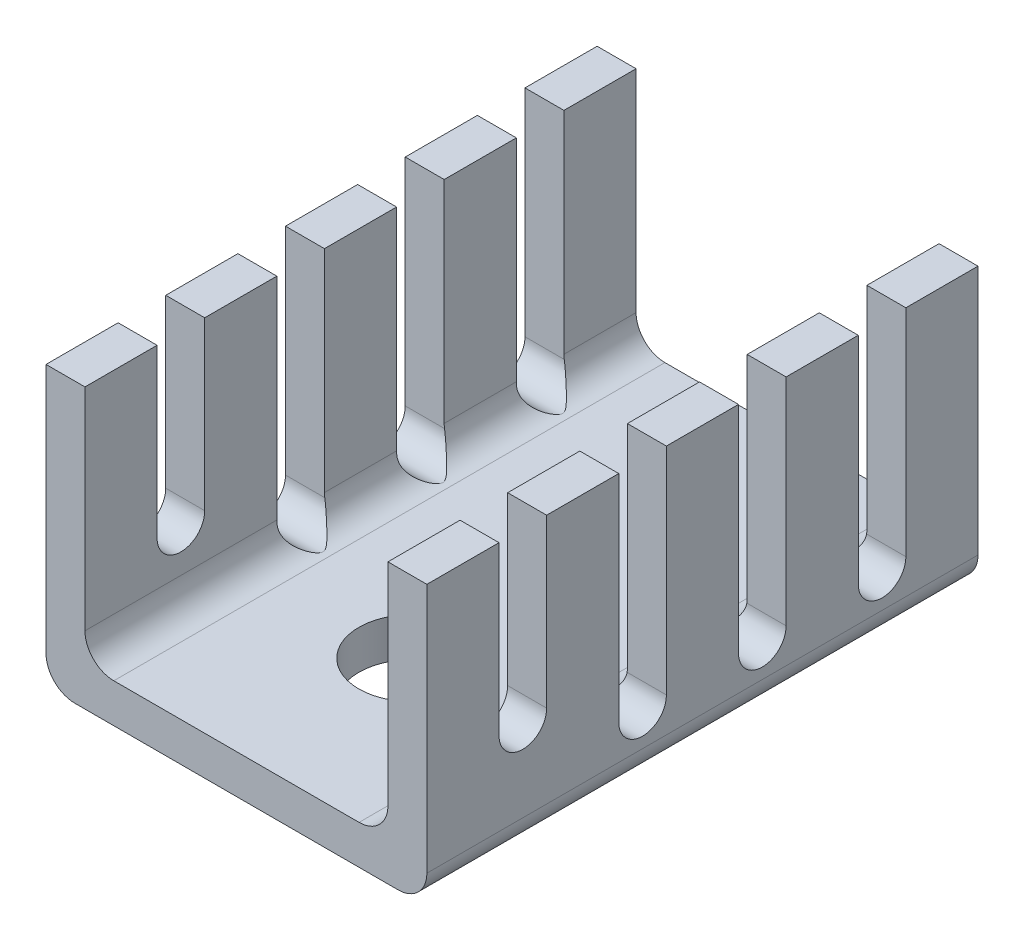
SolidWorks part; units mm, degrees
ref_plane "Front Plane" through (0, 0, 0) normal (0, 0, 1) x (1, 0, 0)
ref_plane "Top Plane" through (0, 0, 0) normal (0, 1, 0) x (1, 0, 0)
ref_plane "Right Plane" through (0, 0, 0) normal (1, 0, 0) x (0, 0, -1)
sketch "Sketch1" plane through (0, 0, 0) normal (0, 0, 1) x (1, 0, 0)
  line L0 (-5.6, 0) -> (5.6, 0)
  line L1 (6.6, 1) -> (6.6, 9.67)
  line L2 (6.6, 9.67) -> (5.25, 9.67)
  line L3 (5.25, 9.67) -> (5.25, 2.35)
  line L4 (4.25, 1.35) -> (-4.25, 1.35)
  line L5 (-5.25, 2.35) -> (-5.25, 9.67)
  line L6 (-5.25, 9.67) -> (-6.6, 9.67)
  line L7 (-6.6, 9.67) -> (-6.6, 1)
  arc A0 (-4.25, 1.35) -> (-5.25, 2.35) centre (-4.25, 2.35) cw
  arc A1 (5.25, 2.35) -> (4.25, 1.35) centre (4.25, 2.35) cw
  arc A2 (5.6, 0) -> (6.6, 1) centre (5.6, 1) ccw
  arc A3 (-5.6, 0) -> (-6.6, 1) centre (-5.6, 1) cw
  point P10 (0, 0)
  point P19 (6.6, 0)
  point P22 (-6.6, 0)
  dimension "D5" = 1
  dimension "D6" = 1
  dimension "D1" = 13.2
  dimension "D2" = 9.67
  dimension "D3" = 1.35
  dimension "D4" = 1.35
extrude "Boss-Extrude3" add sketch "Sketch1" against normal blind 19.1
sketch "Sketch3" plane through (0, 1.35, 0) normal (0, 1, 0) x (1, 0, 0)
  circle A0 centre (0.2414, 5.85) radius 1.85
  dimension "D2" = 3.7
  dimension "D1" = 5.85
extrude "Cut-Extrude2" cut sketch "Sketch3" against normal up to next
sketch "Sketch4" plane through (6.6, 0, 0) normal (1, 0, 0) x (0, 0, -1)
  line L0 (2.5, 9.67) -> (2.5, 3.88)
  line L1 (19.1, 0) -> (0, 0) construction
  line L2 (19.1, 9.67) -> (0, 9.67) construction
  line L3 (4.15, 9.67) -> (4.15, 3.88)
  line L4 (6.65, 9.67) -> (6.65, 2.2)
  line L5 (8.3, 9.67) -> (8.3, 2.2)
  line L6 (10.8, 9.67) -> (10.8, 2.2)
  line L7 (12.45, 9.67) -> (12.45, 2.2)
  line L8 (14.95, 9.67) -> (14.95, 2.2)
  line L9 (16.6, 9.67) -> (16.6, 2.2)
  line L10 (19.1, 1) -> (19.1, 9.67) construction
  line L11 (2.5, 9.67) -> (4.15, 9.67)
  line L12 (6.65, 9.67) -> (8.3, 9.67)
  line L13 (10.8, 9.67) -> (12.45, 9.67)
  line L14 (14.95, 9.67) -> (16.6, 9.67)
  arc A1 (2.5, 3.88) -> (4.15, 3.88) centre (3.325, 3.88) ccw
  arc A2 (6.65, 2.2) -> (8.3, 2.2) centre (7.475, 2.2) ccw
  arc A3 (10.8, 2.2) -> (12.45, 2.2) centre (11.625, 2.2) ccw
  arc A4 (14.95, 2.2) -> (16.6, 2.2) centre (15.775, 2.2) ccw
  dimension "D9" = 3.88
  dimension "D10" = 2.2
  dimension "D1" = 1.65
  dimension "D2" = 1.65
  dimension "D3" = 1.65
  dimension "D4" = 1.65
  dimension "D5" = 2.5
  dimension "D6" = 2.5
  dimension "D7" = 2.5
  dimension "D8" = 2.5
extrude "Cut-Extrude3" cut sketch "Sketch4" against normal through all
